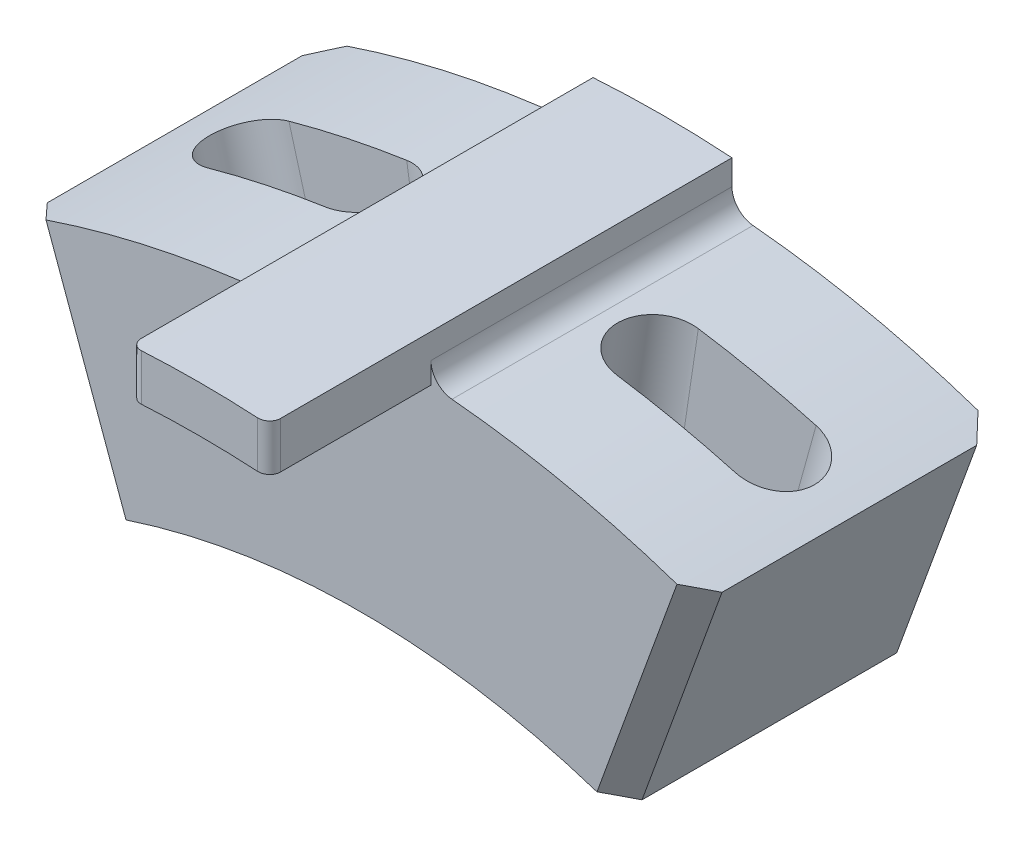
SolidWorks part; units mm, degrees
material "PETG"
ref_plane "Спереди" through (0, 0, 0) normal (0, 0, 1) x (1, 0, 0)
ref_plane "Сверху" through (0, 0, 0) normal (0, 1, 0) x (1, 0, 0)
ref_plane "Справа" through (0, 0, 0) normal (1, 0, 0) x (0, 0, -1)
sketch "Эскиз1" plane through (0, 0, 0) normal (0, 0, 1) x (1, 0, 0)
  line L0 (11.1157, 30.54) -> (14.5701, 40.0309)
  line L1 (-11.1157, 30.54) -> (-14.5701, 40.0309)
  line L2 (0, 0) -> (0, 84.5239) construction
  line L3 (-3, 44.499) -> (-3, 42.4942)
  line L4 (3, 44.499) -> (3, 42.4942)
  arc A0 (11.1157, 30.54) -> (-11.1157, 30.54) centre (0, 0) ccw
  arc A1 (3, 44.499) -> (-3, 44.499) centre (0, 0) ccw
  arc A2 (14.5701, 40.0309) -> (3, 42.4942) centre (0, 0) ccw
  circle A3 centre (0, 0) radius 44.6 construction
  circle A4 centre (0, 0) radius 32.5 construction
  arc A5 (-3, 42.4942) -> (-14.5701, 40.0309) centre (0, 0) ccw
  arc A7 (14.5701, 40.0309) -> (-14.5701, 40.0309) centre (0, 0) ccw construction
  point P6 (59.769, 18.2732)
  point P7 (70, 0)
  dimension "D1" = 65
  dimension "D4" = 10.1
  dimension "D3" = 20
  dimension "D5" = 6
  dimension "D2" = 12.1
extrude "Бобышка-Вытянуть1" add sketch "Эскиз1" along normal mid plane 13
sketch "Эскиз2" plane through (0, 0, 6.5) normal (0, 0, 1) x (1, 0, 0)
  line L0 (3, 42.4942) -> (3, 44.499) construction
  line L1 (-3, 44.499) -> (-3, 42.4942) construction
  line L2 (3, 42.4942) -> (3, 44.499)
  line L3 (-3, 44.499) -> (-3, 42.4942)
  arc A0 (3, 44.499) -> (-3, 44.499) centre (0, 0) ccw construction
  arc A1 (3, 44.499) -> (-3, 44.499) centre (0, 0) ccw
  arc A2 (2.8655, 42.5035) -> (-2.8655, 42.5035) centre (0, 0) ccw construction
  arc A6 (3, 42.4942) -> (-3, 42.4942) centre (0, 0) ccw
  dimension "D1" = 2
extrude "Бобышка-Вытянуть2" add sketch "Эскиз2" along normal blind 7
sketch "Эскиз4" plane through (0, 0, 0) normal (0, 0, 1) x (1, 0, 0)
  line L0 (0, 0) -> (11.3844, 41.0507) construction
  line L1 (13.7121, 42.8957) -> (8.3673, 23.6231)
  line L4 (8.3673, 23.6231) -> (6.681, 24.0908)
  line L5 (13.7121, 42.8957) -> (12.0257, 43.3634)
  line L6 (6.681, 24.0908) -> (12.0257, 43.3634)
  line L7 (0, 0) -> (0, 32.5) construction
  arc A0 (14.5701, 40.0309) -> (3, 42.4942) centre (0, 0) ccw construction
  arc A1 (11.1157, 30.54) -> (-11.1157, 30.54) centre (0, 0) ccw construction
  dimension "D1" = 3.5
  dimension "D2" = 15.5
  dimension "D3" = 25
  dimension "D4" = 20
  dimension "D5" = 1.5924
revolve "Вырез-Повернуть1" cut sketch "Эскиз4" angle 360 about L0
pattern_circular "Круговой массив1" count 2 every 7 about axis through (0, 0, 6.5) along (0, 0, -1) of "Вырез-Повернуть1"
sketch "Эскиз6" plane through (0, 0, 0) normal (0, 0, 1) x (1, 0, 0)
  line L0 (4.8038, 32.143) -> (6.2967, 42.1321)
  line L1 (8.6852, 31.318) -> (11.3844, 41.0507)
  arc A0 (11.1157, 30.54) -> (-11.1157, 30.54) centre (0, 0) ccw construction
  arc A1 (14.5701, 40.0309) -> (3, 42.4942) centre (0, 0) ccw construction
  arc A2 (8.6852, 31.318) -> (4.8038, 32.143) centre (0, 0) ccw
  arc A3 (11.3844, 41.0507) -> (6.2967, 42.1321) centre (0, 0) ccw
  arc A5 (6.5276, 31.8377) -> (3.0661, 32.3551) centre (0, 0) ccw construction
  arc A6 (10.359, 30.8049) -> (6.9863, 31.7402) centre (0, 0) ccw construction
  arc A10 (8.0221, 41.8378) -> (4.5606, 42.3552) centre (0, 0) ccw construction
  arc A12 (13.0611, 40.5483) -> (9.6884, 41.4837) centre (0, 0) ccw construction
extrude "Вырез-Вытянуть2" cut sketch "Эскиз6" against normal mid plane 3.5
mirror "Зеркальное отражение1" about plane through (0, 0, 0) normal (1, 0, 0) of "Вырез-Вытянуть2", "Круговой массив1", "Вырез-Повернуть1"
fillet "Скругление1" radius 1 2 edges at (-3, 42.4942, 0) (3, 42.4942, 0)
chamfer "Фаска1" distance 1 angle 45 4 edges at (12.8429, 35.2855, 6.5) (-12.8429, 35.2855, 6.5) (-12.8429, 35.2855, -6.5) (12.8429, 35.2855, -6.5)
fillet "Скругление2" radius 0.5 2 edges at (3, 43.4966, 13.5) (-3, 43.4966, 13.5)
